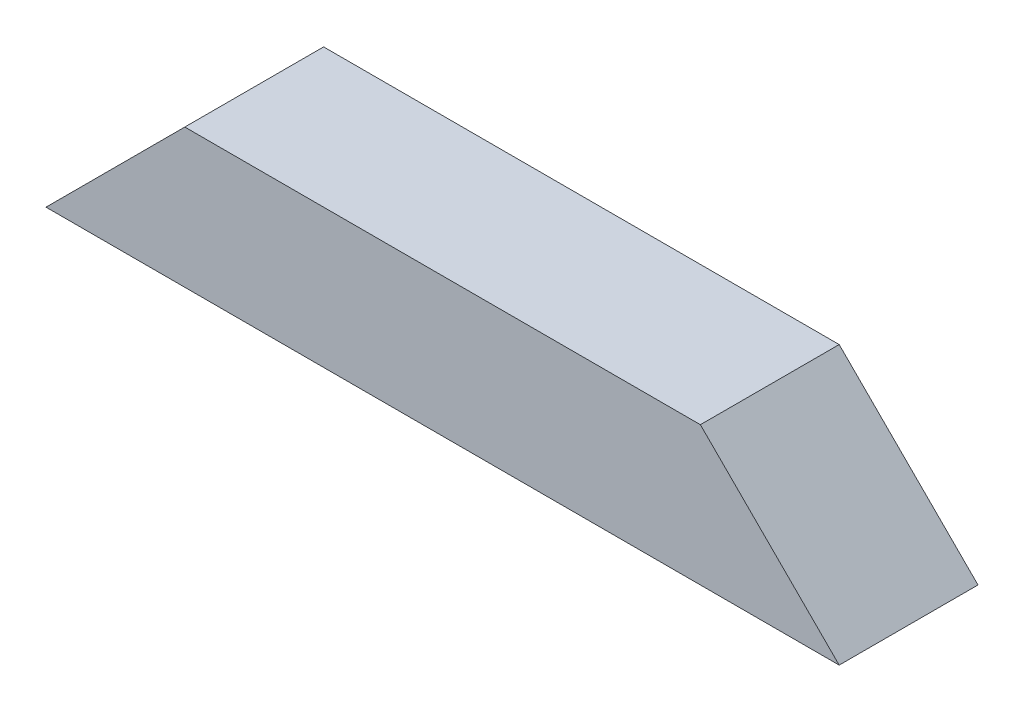
SolidWorks part; units mm, degrees
material "Pine"
ref_plane "Front Plane" through (0, 0, 0) normal (0, 0, 1) x (1, 0, 0)
ref_plane "Top Plane" through (0, 0, 0) normal (0, 1, 0) x (1, 0, 0)
ref_plane "Right Plane" through (0, 0, 0) normal (1, 0, 0) x (0, 0, -1)
sketch "Sketch1" plane through (0, 0, 0) normal (0, 0, 1) x (1, 0, 0)
  line L0 (508, 0) -> (419.1, 88.9)
  line L1 (0, 0) -> (508, 0)
  line L2 (0, 0) -> (0, 88.9)
  line L3 (0, 88.9) -> (508, 88.9)
  line L4 (508, 0) -> (508, 88.9)
  line L5 (0, 0) -> (88.9, 88.9)
  dimension "D1" = 508
  dimension "D2" = 88.9
  dimension "D3" = 45
  dimension "D4" = 45
extrude "Boss-Extrude1" add sketch "Sketch1" against normal blind 88.9 contours L5 L1 L0 L3
